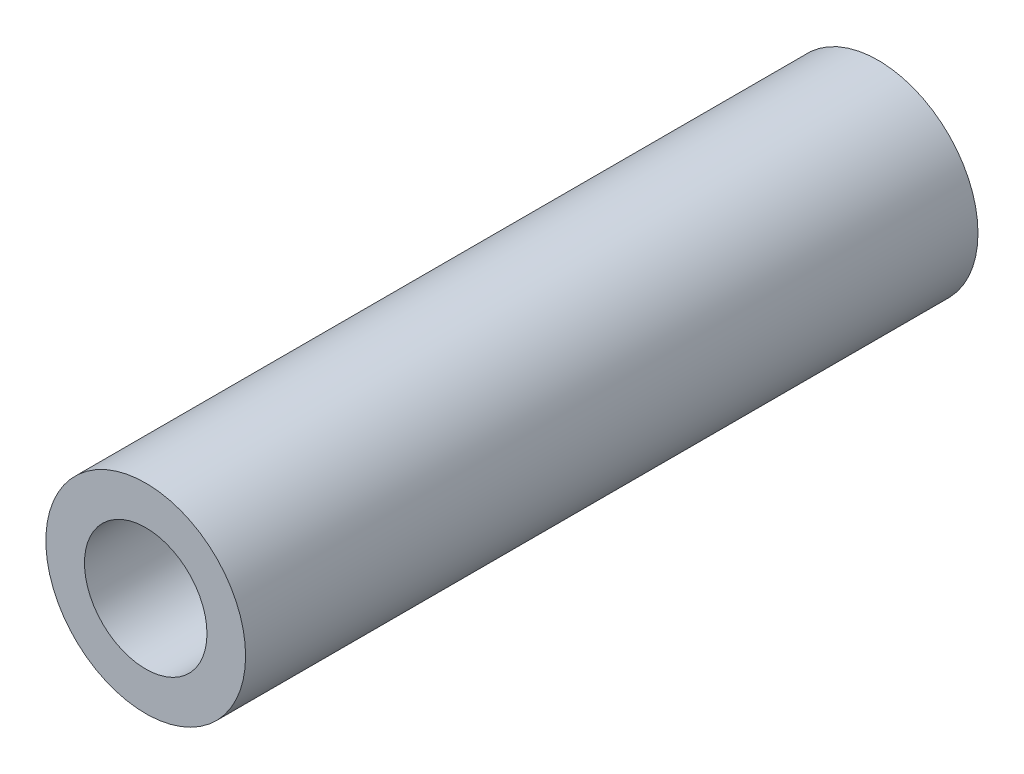
SolidWorks part; units mm, degrees
ref_plane "Front Plane" through (0, 0, 0) normal (0, 0, 1) x (1, 0, 0)
ref_plane "Top Plane" through (0, 0, 0) normal (0, 1, 0) x (1, 0, 0)
ref_plane "Right Plane" through (0, 0, 0) normal (1, 0, 0) x (0, 0, -1)
sketch "Sketch1" plane through (0, 0, 0) normal (0, 0, 1) x (1, 0, 0)
  circle A0 centre (0, 0) radius 2.3812
  circle A1 centre (0, 0) radius 1.4605
  dimension "OD" = 4.7625
  dimension "ID" = 2.921
extrude "Extrude1" add sketch "Sketch1" along normal mid plane 17.4625
sketch "Sketch2" plane through (0, 0, 0) normal (1, 0, 0) x (0, 0, -1)
  line L0 (-8.7312, -1.4605) -> (8.7312, -1.4605) construction
  line L3 (8.7312, 1.4605) -> (-8.7312, 1.4605) construction
  line L5 (-8.7312, -1.4605) -> (8.7312, -1.4605)
  line L6 (8.7312, 1.4605) -> (-8.7312, 1.4605)
sketch "Sketch4" plane through (0, 0, 8.7312) normal (0, 0, 1) x (1, 0, 0)
  line L0 (0, 0) -> (-1.0327, 1.0327)
  line L1 (0, -2.6194) -> (0, 2.6194) construction
  circle A0 centre (0, 0) radius 1.4605 construction
  dimension "D1" = 45
